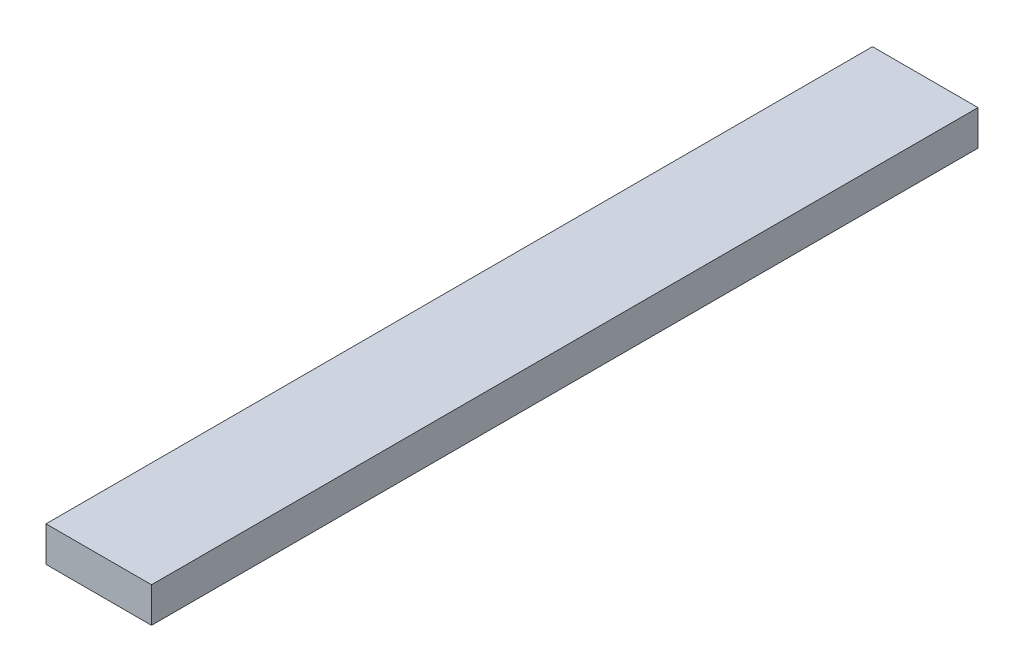
SolidWorks part; units mm, degrees
material "Сосна"
ref_plane "Спереди" through (0, 0, 0) normal (0, 0, 1) x (1, 0, 0)
ref_plane "Сверху" through (0, 0, 0) normal (0, 1, 0) x (1, 0, 0)
ref_plane "Справа" through (0, 0, 0) normal (1, 0, 0) x (0, 0, -1)
sketch "Эскиз1" plane through (0, 0, 0) normal (0, 0, 1) x (1, 0, 0)
  line L1 (0, 0) -> (60, 0)
  line L2 (0, 0) -> (0, 20)
  line L3 (0, 20) -> (60, 20)
  line L4 (60, 0) -> (60, 20)
  dimension "D1" = 20
  dimension "D2" = 60
extrude "Бобышка-Вытянуть1" add sketch "Эскиз1" against normal blind 470
